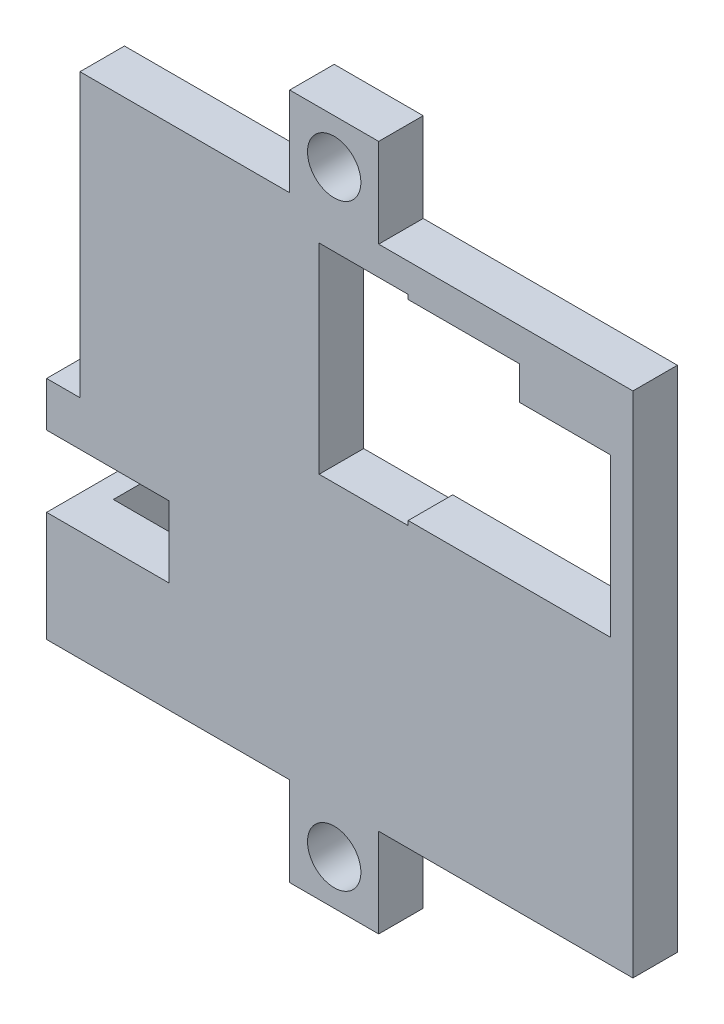
SolidWorks part; units mm, degrees
ref_plane "Front Plane" through (0, 0, 0) normal (1, 0, 0) x (0, 1, 0)
ref_plane "Top Plane" through (0, 0, 0) normal (0, 0, 1) x (0, 1, 0)
ref_plane "Right Plane" through (0, 0, 0) normal (0, 1, 0) x (-1, 0, 0)
sketch "Sketch2" plane through (0, 0, 0) normal (0, 0, 1) x (0, 1, 0)
  line L1 (-11.425, 11.425) -> (11.425, 11.425)
  line L2 (-11.425, 11.425) -> (-11.425, -11.425)
  line L3 (-11.425, -11.425) -> (11.425, -11.425)
  line L4 (11.425, 11.425) -> (11.425, -11.425)
  line L5 (-11.425, 11.425) -> (11.425, -11.425) construction
  line L6 (-11.425, -11.425) -> (11.425, 11.425) construction
  point P0 (0, 0)
  dimension "D1" = 22.85
extrude "Boss-Extrude1" add sketch "Sketch2" along normal blind 2
sketch "Sketch3" plane through (0, 0, 2) normal (0, 0, 1) x (1, 0, 0)
  line L0 (0, 0) -> (0, 13.425) construction
  line L1 (11.425, 11.425) -> (-11.425, 11.425) construction
  line L2 (-11.425, 0) -> (0, 0) construction
  line L3 (-2, 15.425) -> (2, 15.425)
  line L4 (-2, 15.425) -> (-2, 11.425)
  line L5 (-2, 11.425) -> (2, 11.425)
  line L6 (2, 15.425) -> (2, 11.425)
  line L7 (-2, 15.425) -> (2, 11.425) construction
  line L8 (-2, 11.425) -> (2, 15.425) construction
  line L9 (-11.425, 11.425) -> (-11.425, -11.425) construction
  line L10 (-2, -11.425) -> (2, -15.425) construction
  line L11 (-2, -15.425) -> (2, -11.425) construction
  line L12 (2, -15.425) -> (2, -11.425)
  line L13 (-2, -11.425) -> (2, -11.425)
  line L14 (-2, -15.425) -> (-2, -11.425)
  line L15 (-2, -15.425) -> (2, -15.425)
  dimension "D1" = 2
extrude "Boss-Extrude2" add sketch "Sketch3" against normal up to surface (2 mm away) up to face at (0, 0, 0)
sketch "Sketch4" plane through (0, 0, 2) normal (0, 0, 1) x (1, 0, 0)
  line L0 (-2, 13.425) -> (2, 13.425) construction
  line L1 (-2, 15.425) -> (-2, 11.425) construction
  line L2 (2, 11.425) -> (2, 15.425) construction
  line L3 (0, 15.425) -> (0, 13.425) construction
  line L4 (2, 15.425) -> (-2, 15.425) construction
  line L5 (-11.425, 0) -> (11.425, 0) construction
  line L6 (-11.425, 11.425) -> (-11.425, -11.425) construction
  line L7 (11.425, -11.425) -> (11.425, 11.425) construction
  line L8 (0, -15.425) -> (0, -13.425) construction
  line L9 (-2, -13.425) -> (2, -13.425) construction
hole_wizard "M2 Clearance Hole1" positions "Sketch5" profile "Sketch6" hole size "M2" standard "ISO" end condition through all
sketch "Sketch5" plane through (0, 0, 2) normal (0, 0, 1) x (1, 0, 0)
  line L0 (-2, 13.425) -> (2, 13.425) construction
  point P0 (0, 13.425)
  point P4 (0, -13.425)
sketch "Sketch6" plane through (0, 13.425, 2) normal (1, 0, 0) x (0, -1, 0)
  line L0 (0, 0) -> (0, 2)
  line L1 (0, 2) -> (1.2, 2)
  line L2 (1.2, 2) -> (1.2, 0)
  line L5 (1.2, 0) -> (0, 0)
  line L11 (0, -6.35) -> (0, 107.95) construction
  dimension "Thru Hole Dia." = 2.4
  dimension "Thru Hole Depth" = 2
sketch "Sketch7" plane through (0, 0, 2) normal (0, 0, 1) x (1, 0, 0)
  line L0 (11.425, -11.425) -> (11.425, 4.8814) construction
  line L1 (11.425, -11.425) -> (11.425, 11.425) construction
  line L2 (11.425, 8.4314) -> (11.425, 1.3314)
  line L3 (11.425, 8.4314) -> (8.325, 8.4314)
  line L5 (3.325, 1.3314) -> (11.425, 1.3314)
  line L7 (3.325, 10.1314) -> (-0.675, 10.1314)
  line L8 (-0.675, 10.1314) -> (-0.675, 1.1314)
  line L9 (-0.675, 1.1314) -> (3.325, 1.1314)
  line L10 (3.325, 1.1314) -> (3.325, 1.3314)
  line L11 (3.325, 9.9314) -> (8.325, 9.9314)
  line L12 (8.325, 9.9314) -> (8.325, 8.4314)
  line L13 (3.325, 10.1314) -> (3.325, 9.9314)
  point P8 (11.425, 4.8814)
  dimension "D1" = 16.3064
  dimension "D2" = 7.1
  dimension "D3" = 9
  dimension "D5" = 4
  dimension "D6" = 5
  dimension "D7" = 1.5
extrude "Cut-Extrude3" cut sketch "Sketch7" against normal up to next
sketch "Sketch8" plane through (0, 0, 2) normal (0, 0, 1) x (1, 0, 0)
  line L0 (-11.425, 11.425) -> (-11.425, -4.875) construction
  line L1 (-11.425, 11.425) -> (-11.425, -11.425) construction
  line L2 (-11.425, -3.275) -> (-11.425, -6.475)
  line L3 (-11.425, -3.275) -> (-7.425, -3.275)
  line L4 (-7.425, -3.275) -> (-7.425, -6.475)
  line L5 (-7.425, -6.475) -> (-11.425, -6.475)
  point P8 (-11.425, -4.875)
  dimension "D1" = 16.3
  dimension "D2" = 3.2
  dimension "D3" = 4
extrude "Cut-Extrude4" cut sketch "Sketch8" against normal up to next
sketch "Sketch10" plane through (-11.425, 0, 0) normal (-1, 0, 0) x (0, -1, 0)
  line L0 (-11.425, 0) -> (3.275, 0) construction
  line L1 (6.475, 2) -> (11.425, 2)
  line L2 (6.475, 2) -> (6.475, 0)
  line L3 (6.475, 0) -> (11.425, 0)
  line L4 (11.425, 2) -> (11.425, 0)
  line L5 (3.275, 2) -> (1.2639, 2)
  line L6 (3.275, 2) -> (3.275, 0)
  line L7 (3.275, 0) -> (1.2639, 0)
  line L8 (1.2639, 2) -> (1.2639, 0)
extrude "Boss-Extrude3" add sketch "Sketch10" along normal blind 1.5 contours L6 L5 L8 L7 | L2 L1 L4 L3
sketch "Sketch11" plane through (0, 0, 0) normal (0, 0, -1) x (1, 0, 0)
  line L0 (-7.425, 6.475) -> (-12.925, 6.475) construction
  line L1 (-12.925, 11.425) -> (-11.925, 11.425)
  line L2 (-12.925, 11.425) -> (-12.925, 6.475)
  line L3 (-12.925, 6.475) -> (-11.925, 6.475)
  line L4 (-11.925, 11.425) -> (-11.925, 6.475)
  line L5 (-12.925, 1.2639) -> (-11.425, 1.2639) construction
  line L6 (-12.925, 3.275) -> (-11.925, 3.275)
  line L7 (-12.925, 3.275) -> (-12.925, 1.2639)
  line L8 (-12.925, 1.2639) -> (-11.925, 1.2639)
  line L9 (-11.925, 3.275) -> (-11.925, 1.2639)
  dimension "D1" = 1
  dimension "D2" = 1
extrude "Boss-Extrude4" add sketch "Sketch11" along normal blind 4
sketch "Sketch12" plane through (11.425, 0, 0) normal (1, 0, 0) x (0, 1, 0)
  line L1 (8.4314, 2) -> (11.425, 2)
  line L2 (8.4314, 2) -> (8.4314, 0)
  line L3 (8.4314, 0) -> (11.425, 0)
  line L4 (11.425, 2) -> (11.425, 0)
  line L5 (-11.425, 2) -> (1.3314, 2)
  line L6 (-11.425, 2) -> (-11.425, 0)
  line L7 (-11.425, 0) -> (1.3314, 0)
  line L8 (1.3314, 2) -> (1.3314, 0)
extrude "Boss-Extrude5" add sketch "Sketch12" along normal blind 2
sketch "Sketch13" plane through (0, 1.3314, 0) normal (0, 1, 0) x (-1, 0, 0)
  line L0 (-13.425, 0) -> (-2, 0) construction
  line L1 (-13.425, 2) -> (-12.425, 2)
  line L2 (-13.425, 2) -> (-13.425, 0)
  line L3 (-13.425, 0) -> (-12.425, 0)
  line L4 (-12.425, 2) -> (-12.425, 0)
  dimension "D1" = 1
extrude "Boss-Extrude6" add sketch "Sketch13" along normal up to surface (7.1 mm away) up to face at (10.875, 8.4314, 1)
sketch "Sketch15" plane through (0, 0, 0) normal (0, 0, -1) x (1, 0, 0)
  line L0 (-12.425, 6.475) -> (-12.425, 3.275) construction
  line L1 (-12.925, 6.475) -> (-11.925, 6.475) construction
  line L2 (-11.925, 3.275) -> (-12.925, 3.275) construction
  line L3 (-12.425, 4.875) -> (-1.425, 4.875) construction
  line L4 (-1.425, 4.875) -> (6.575, 4.875) construction
  line L5 (-7.425, 4.875) -> (-7.425, -2.625) construction
  line L6 (-7.425, 3.275) -> (-7.425, 6.475) construction
  circle A0 centre (-1.425, 4.875) radius 1
  circle A1 centre (6.575, 4.875) radius 1
  circle A2 centre (-7.425, -2.625) radius 1
  dimension "D3" = 2
  dimension "D1" = 11
  dimension "D2" = 8
  dimension "D4" = 7.5
extrude "Boss-Extrude7" add sketch "Sketch15" along normal blind 2.5 contours A2 | A1 | A0
chamfer "Chamfer1" distance 0.5 angle 45 3 edges at (-8.425, 2.625, -2.5) (5.575, -4.875, -2.5) (-2.425, -4.875, -2.5)
